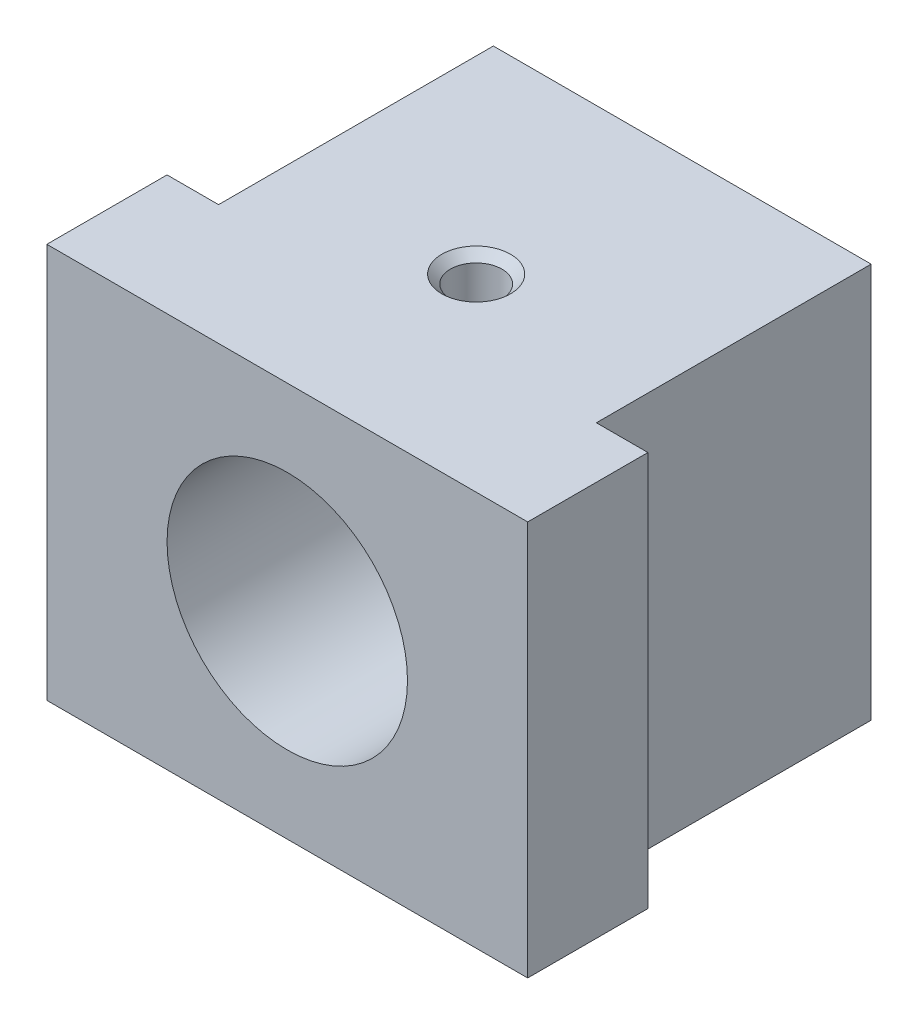
SolidWorks part; units mm, degrees
ref_plane "Front Plane" through (0, 0, 0) normal (0, 0, 1) x (1, 0, 0)
ref_plane "Top Plane" through (0, 0, 0) normal (0, 1, 0) x (1, 0, 0)
ref_plane "Right Plane" through (0, 0, 0) normal (1, 0, 0) x (0, 0, -1)
sketch "Sketch1" plane through (0, 0, 0) normal (0, 1, 0) x (1, 0, 0)
  line L0 (0, 0) -> (28, 0)
  line L1 (28, 0) -> (28, 7)
  line L2 (28, 7) -> (25, 7)
  line L3 (25, 7) -> (25, 23)
  line L4 (25, 23) -> (3, 23)
  line L5 (3, 23) -> (3, 7)
  line L6 (3, 7) -> (0, 7)
  line L7 (0, 7) -> (0, 0)
  dimension "D1" = 7
  dimension "D2" = 16
  dimension "D3" = 22
  dimension "D4" = 28
  dimension "D5" = 3
extrude "Boss-Extrude1" add sketch "Sketch1" along normal blind 23
sketch "Sketch2" plane through (0, 0, 0) normal (0, 0, 1) x (1, 0, 0)
  line L0 (14, 11.5) -> (14, 23) construction
  line L1 (0, 23) -> (28, 23) construction
  line L2 (14, 11.5) -> (0, 11.5) construction
  line L3 (0, 23) -> (0, 0) construction
  circle A0 centre (14, 11.5) radius 7
  dimension "D1" = 14
extrude "Cut-Extrude1" cut sketch "Sketch2" against normal through all
sketch "Sketch3" plane through (0, 23, 0) normal (0, 1, 0) x (1, 0, 0)
  line L0 (14, 0) -> (14, 11) construction
  line L1 (0, 0) -> (28, 0) construction
  circle A0 centre (14, 11) radius 1.5
  dimension "D1" = 3
  dimension "D2" = 11
extrude "Cut-Extrude2" cut sketch "Sketch3" against normal blind 10 contours A0
chamfer "Chamfer1" distance 0.5 angle 45 1 edges at (14, 23, -9.5)
